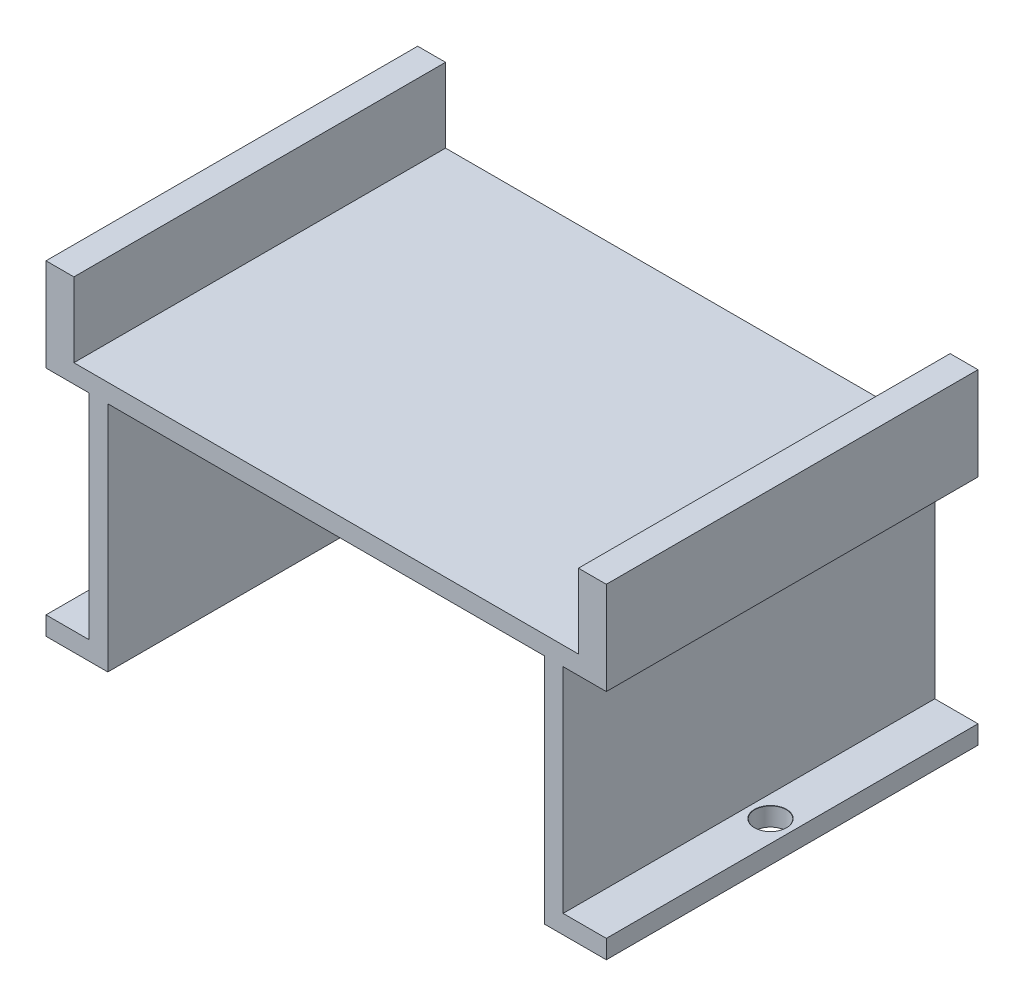
SolidWorks part; units mm, degrees
ref_plane "Front Plane" through (0, 0, 0) normal (0, 0, 1) x (1, 0, 0)
ref_plane "Top Plane" through (0, 0, 0) normal (0, 1, 0) x (1, 0, 0)
ref_plane "Right Plane" through (0, 0, 0) normal (1, 0, 0) x (0, 0, -1)
sketch "Sketch1" plane through (0, 0, 0) normal (0, 0, 1) x (1, 0, 0)
  line L1 (-30.15, 17.5) -> (30.15, 17.5)
  line L2 (-30.15, 17.5) -> (-30.15, -17.5)
  line L3 (-30.15, -17.5) -> (30.15, -17.5)
  line L4 (30.15, 17.5) -> (30.15, -17.5)
  line L5 (-30.15, 17.5) -> (30.15, -17.5) construction
  line L6 (-30.15, -17.5) -> (30.15, 17.5) construction
  point P0 (0, 0)
  dimension "D1" = 35
  dimension "D2" = 60.3
extrude "Boss-Extrude1" add sketch "Sketch1" along normal blind 40
sketch "Sketch2" plane through (0, 0, 0) normal (0, 0, -1) x (-1, 0, 0)
  line L0 (30.15, -17.5) -> (-30.15, -17.5) construction
  line L5 (-23.5, 7.5) -> (23.5, 7.5)
  line L6 (-23.5, 7.5) -> (-23.5, -17.5)
  line L7 (-23.5, -17.5) -> (23.5, -17.5)
  line L8 (23.5, 7.5) -> (23.5, -17.5)
  line L9 (-30.15, 17.5) -> (30.15, 17.5) construction
  line L10 (-27.15, 17.5) -> (27.15, 17.5)
  line L11 (-27.15, 17.5) -> (-27.15, 9.5)
  line L12 (-27.15, 9.5) -> (27.15, 9.5)
  line L13 (27.15, 17.5) -> (27.15, 9.5)
  line L14 (-30.15, -17.5) -> (-30.15, 17.5) construction
  line L15 (30.15, 17.5) -> (30.15, -17.5) construction
  line L17 (-30.15, 7.5) -> (-25.5, 7.5)
  line L18 (-30.15, 7.5) -> (-30.15, -15.5)
  line L19 (-30.15, -15.5) -> (-25.5, -15.5)
  line L20 (-25.5, 7.5) -> (-25.5, -15.5)
  line L21 (30.15, 7.5) -> (25.5, 7.5)
  line L22 (30.15, 7.5) -> (30.15, -15.5)
  line L23 (30.15, -15.5) -> (25.5, -15.5)
  line L24 (25.5, 7.5) -> (25.5, -15.5)
  dimension "D1" = 25
  dimension "D2" = 3
  dimension "D3" = 8
  dimension "D4" = 3
  dimension "D5" = 4.65
  dimension "D6" = 2
  dimension "D7" = 2
  dimension "D8" = 2
  dimension "D9" = 4.65
  dimension "D10" = 2
  dimension "D11" = 2
  dimension "D12" = 2
extrude "Cut-Extrude1" cut sketch "Sketch2" against normal through all
hole_wizard "M3 Clearance Hole2" positions "Sketch13" profile "Sketch14" hole size "M3" standard "ISO"
sketch "Sketch13" plane through (0, -15.5, 0) normal (0, 1, 0) x (1, 0, 0)
  line L0 (-25.5, 0) -> (-30.15, 0) construction
  line L1 (-30.15, -40) -> (-30.15, 0) construction
  point P0 (-27.82, -20)
  dimension "D1" = 20
  dimension "D2" = 2.33
sketch "Sketch14" plane through (-27.82, -15.5, 20) normal (1, 0, 0) x (0, 0, 1)
  line L0 (0, 0) -> (0, 2)
  line L1 (0, 2) -> (1.7, 2)
  line L2 (1.7, 2) -> (1.7, 0.025)
  line L3 (1.7, 0.025) -> (1.725, 0)
  line L5 (1.725, 0) -> (0, 0)
  line L6 (-1.7, 0.025) -> (-1.725, 0) construction
  line L11 (0, -6.35) -> (0, 107.95) construction
  dimension "Thru Hole Dia." = 3.4
  dimension "Thru Hole Depth" = 2
  dimension "Near C'Sink Dia." = 3.45
  dimension "Near C'Sink Angle" = 90
hole_wizard "M3 Clearance Hole3" positions "Sketch15" profile "Sketch16" hole size "M3" standard "ISO"
sketch "Sketch15" plane through (0, -15.5, 0) normal (0, 1, 0) x (1, 0, 0)
  line L0 (30.15, 0) -> (25.5, 0) construction
  line L1 (30.15, -40) -> (30.15, 0) construction
  point P0 (27.82, -20)
  dimension "D1" = 20
  dimension "D2" = 2.33
sketch "Sketch16" plane through (27.82, -15.5, 20) normal (1, 0, 0) x (0, 0, 1)
  line L0 (0, 0) -> (0, 2)
  line L1 (0, 2) -> (1.7, 2)
  line L2 (1.7, 2) -> (1.7, 0.025)
  line L3 (1.7, 0.025) -> (1.725, 0)
  line L5 (1.725, 0) -> (0, 0)
  line L6 (-1.7, 0.025) -> (-1.725, 0) construction
  line L11 (0, -6.35) -> (0, 107.95) construction
  dimension "Thru Hole Dia." = 3.4
  dimension "Thru Hole Depth" = 2
  dimension "Near C'Sink Dia." = 3.45
  dimension "Near C'Sink Angle" = 90
